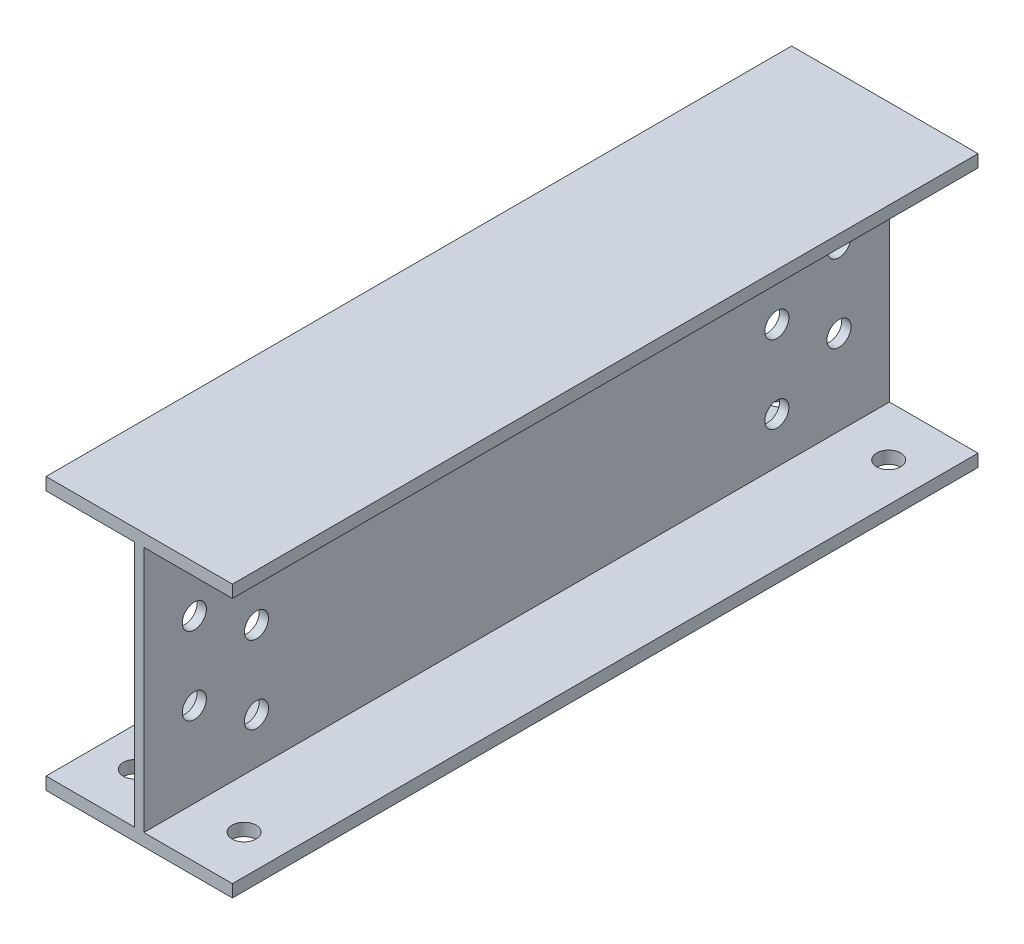
SolidWorks part; units mm, degrees
ref_plane "前视基准面" through (0, 0, 0) normal (0, 0, 1) x (1, 0, 0)
ref_plane "上视基准面" through (0, 0, 0) normal (0, 1, 0) x (1, 0, 0)
ref_plane "右视基准面" through (0, 0, 0) normal (1, 0, 0) x (0, 0, -1)
sketch "草图1" plane through (0, 0, 0) normal (0, 0, 1) x (1, 0, 0)
  line L0 (-6, 159) -> (-120, 159)
  line L1 (-120, 159) -> (-120, 175)
  line L2 (-120, 175) -> (120, 175)
  line L3 (120, 175) -> (120, 159)
  line L4 (120, 159) -> (6, 159)
  line L5 (6, 159) -> (6, -159)
  line L6 (6, -159) -> (120, -159)
  line L7 (120, -159) -> (120, -175)
  line L8 (120, -175) -> (-120, -175)
  line L9 (-120, -175) -> (-120, -159)
  line L10 (-120, -159) -> (-6, -159)
  line L11 (-6, -159) -> (-6, 159)
  line L12 (-1000, 0) -> (-886, 0) construction
  line L16 (0, 71.1058) -> (0, -85.9124) construction
  dimension "D1" = 350
  dimension "D2" = 240
  dimension "D3" = 12
  dimension "D4" = 16
extrude "拉伸1" add sketch "草图1" along normal mid plane 960
sketch "草图2" plane through (0, 0, 0) normal (1, 0, 0) x (0, 0, -1)
  line L0 (-480, -159) -> (-480, 159) construction
  line L1 (-480, 175) -> (480, 175) construction
  line L2 (335, 100) -> (335, 0) construction
  line L3 (0, 386.6401) -> (0, -341.8233) construction
  line L4 (-335, 100) -> (-335, 0) construction
  circle A0 centre (-415, 50) radius 15.5
  circle A1 centre (-335, 100) radius 15.5
  circle A2 centre (-335, 0) radius 15.5
  circle A3 centre (-335, -100) radius 15.5
  circle A4 centre (-415, -50) radius 15.5
  circle A5 centre (415, -50) radius 15.5
  circle A6 centre (335, -100) radius 15.5
  circle A7 centre (335, 0) radius 15.5
  circle A8 centre (335, 100) radius 15.5
  circle A9 centre (415, 50) radius 15.5
  dimension "D1" = 31
  dimension "D2" = 65
  dimension "D3" = 75
  dimension "D4" = 100
  dimension "D5" = 50
  dimension "D6" = 80
  dimension "D7" = 50
  dimension "D8" = 50
extrude "拉伸2" cut sketch "草图2" against normal through all and the other way through all
sketch "草图5" plane through (0, -159, 0) normal (0, 1, 0) x (1, 0, 0)
  line L0 (0, 0) -> (0, 2071.2487) construction
  line L1 (-6, 480) -> (-120, 480) construction
  line L3 (-563.3076, 0) -> (463.7596, 0) construction
  circle A0 centre (-70, 415) radius 15.5
  circle A1 centre (70, 415) radius 15.5
  circle A2 centre (-70, -415) radius 15.5
  circle A3 centre (70, -415) radius 15.5
  dimension "D1" = 31
  dimension "D2" = 31
  dimension "D3" = 70
  dimension "D4" = 70
  dimension "D5" = 65
extrude "拉伸4" cut sketch "草图5" against normal through all
